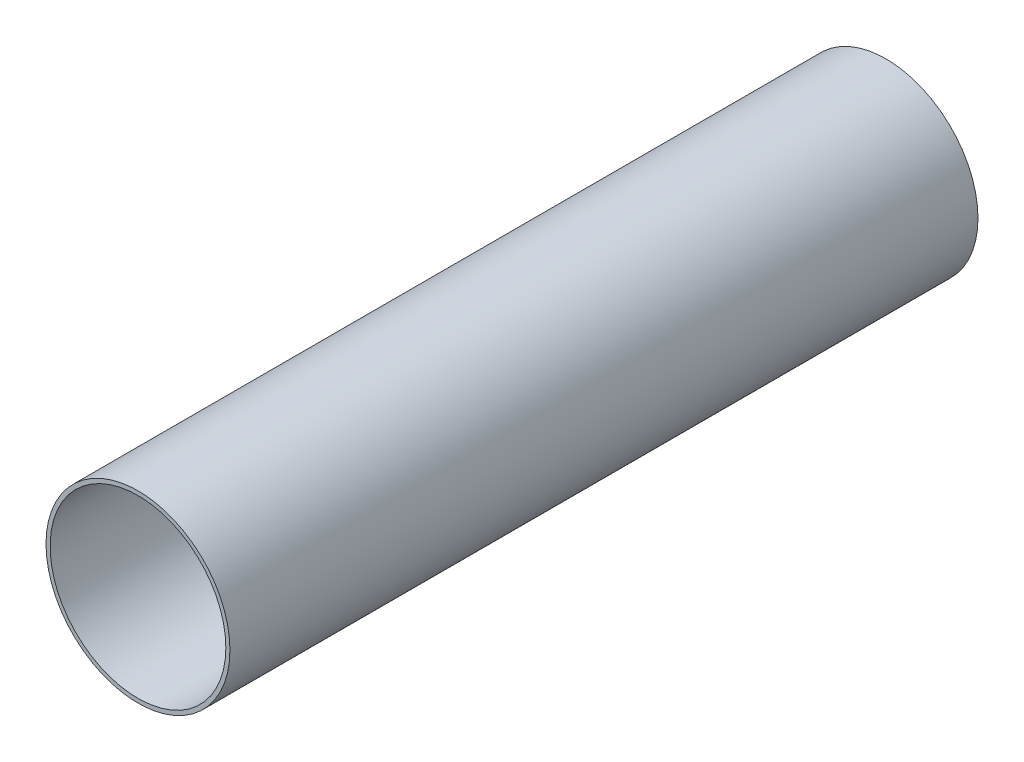
SolidWorks part; units mm, degrees
ref_plane "Front Plane" through (0, 0, 0) normal (1, 0, 0) x (0, 1, 0)
ref_plane "Top Plane" through (0, 0, 0) normal (0, 0, 1) x (0, 1, 0)
ref_plane "Right Plane" through (0, 0, 0) normal (0, 1, 0) x (-1, 0, 0)
sketch "Sketch1" plane through (0, 0, 0) normal (0, 0, 1) x (0, 1, 0)
  circle A0 centre (0, 0) radius 32.15
  circle A1 centre (0, 0) radius 33.65
  dimension "D1" = 64.3
  dimension "D2" = 1.5
extrude "Boss-Extrude1" add sketch "Sketch1" along normal blind 273.7
